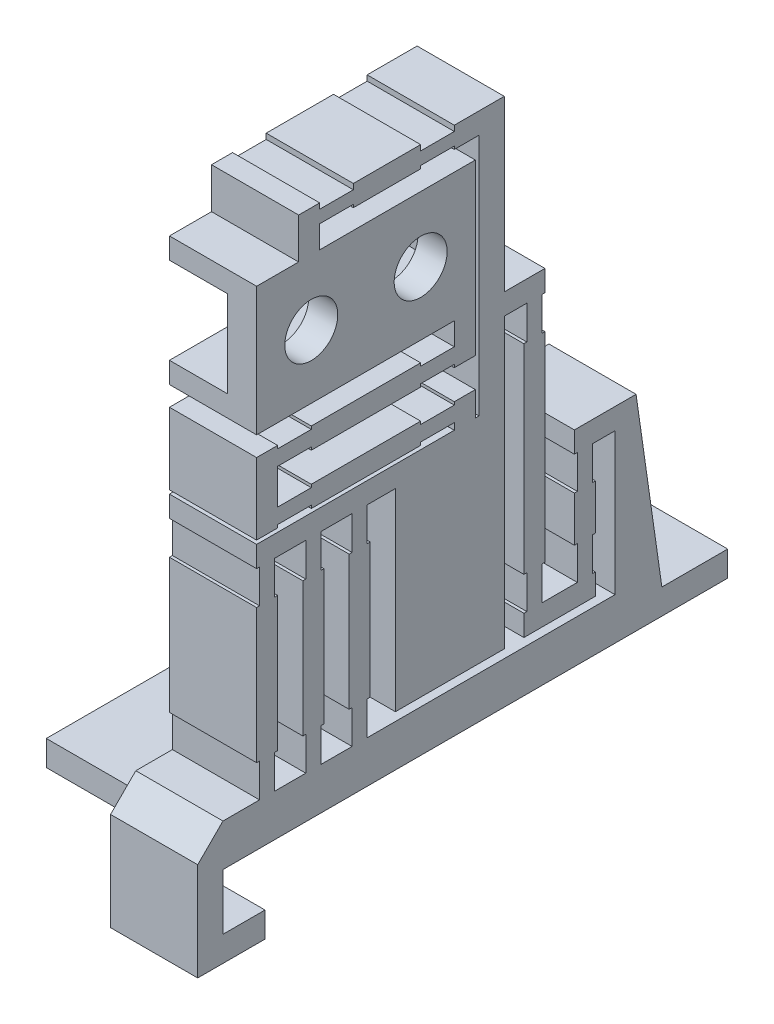
SolidWorks part; units mm, degrees
other "Markup1"
sketch "Sketch8" plane through (10.5, 0, 3) normal (0.7095, 0.0467, 0.7031) x (0.7044, -0.0184, -0.7096)
ref_plane "Front Plane" through (0, 0, 0) normal (0, 0, 1) x (1, 0, 0)
ref_plane "Top Plane" through (0, 0, 0) normal (0, 1, 0) x (1, 0, 0)
ref_plane "Right Plane" through (0, 0, 0) normal (1, 0, 0) x (0, 0, -1)
sketch "Sketch1" plane through (0, 0, 0) normal (1, 0, 0) x (0, 0, -1)
  line L0 (5.75, 29.025) -> (15, 29.025)
  line L1 (15, 29.025) -> (15, 18.9583)
  line L2 (2, 29.025) -> (2, 21.375)
  line L3 (2, 21.375) -> (13.75, 21.375)
  line L56 (13.75, 20.0333) -> (11.75, 20.0333)
  line L57 (3.25, 19.1333) -> (3.25, 17.0333)
  line L58 (3.25, 17.0333) -> (5.25, 17.0333)
  line L59 (15, 17.2083) -> (15, 15.7383)
  line L60 (13.75, 21.375) -> (13.75, 20.0333)
  line L61 (11.75, 20.0333) -> (11.75, 20.2083)
  line L62 (2, 20.2083) -> (2, 15.9583)
  line L63 (5.25, 17.0333) -> (5.25, 17.2083)
  line L64 (15.22, 30.1917) -> (15.22, 15.7383)
  line L65 (5.75, 30.3667) -> (7.75, 30.3667)
  line L66 (13.75, 31.1167) -> (13.75, 31.4417)
  line L69 (5.75, 29.025) -> (5.75, 30.3667)
  line L70 (7.75, 30.3667) -> (7.75, 30.1917)
  line L76 (7.75, 30.1917) -> (11.75, 30.1917)
  line L77 (11.75, 30.1917) -> (11.75, 30.3667)
  line L78 (11.75, 30.3667) -> (13.75, 30.3667)
  line L79 (13.75, 30.3667) -> (13.75, 30.1917)
  line L80 (13.75, 30.1917) -> (15.22, 30.1917)
  line L81 (13.75, 31.1167) -> (11.75, 31.1167)
  line L82 (11.75, 31.1167) -> (11.75, 31.4417)
  line L83 (11.75, 31.4417) -> (7.75, 31.4417)
  line L84 (7.75, 31.4417) -> (7.75, 31.1167)
  line L85 (7.75, 31.1167) -> (5.75, 31.1167)
  line L86 (5.75, 31.1167) -> (5.75, 31.4417)
  line L87 (5.75, 31.4417) -> (4.5, 31.4417)
  line L100 (11.75, 20.2083) -> (5.25, 20.2083)
  line L101 (5.25, 20.2083) -> (5.25, 20.0333)
  line L102 (5.25, 20.0333) -> (3.25, 20.0333)
  line L103 (3.25, 20.0333) -> (3.25, 20.2083)
  line L104 (3.25, 20.2083) -> (2, 20.2083)
  line L105 (15, 18.9583) -> (13.75, 18.9583)
  line L106 (13.75, 18.9583) -> (13.75, 19.1333)
  line L107 (13.75, 19.1333) -> (11.75, 19.1333)
  line L108 (11.75, 19.1333) -> (11.75, 18.9583)
  line L109 (11.75, 18.9583) -> (5.25, 18.9583)
  line L110 (5.25, 18.9583) -> (5.25, 19.1333)
  line L111 (5.25, 19.1333) -> (3.25, 19.1333)
  line L112 (5.25, 17.2083) -> (11.75, 17.2083)
  line L113 (11.75, 17.2083) -> (11.75, 17.0333)
  line L114 (11.75, 17.0333) -> (13.75, 17.0333)
  line L115 (13.75, 17.0333) -> (13.75, 17.2083)
  line L116 (13.75, 17.2083) -> (15, 17.2083)
  line L117 (2, 15.9583) -> (3.25, 15.9583)
  line L118 (3.25, 15.9583) -> (3.25, 16.1333)
  line L119 (3.25, 16.1333) -> (5.25, 16.1333)
  line L120 (5.25, 16.1333) -> (5.25, 15.9583)
  line L121 (5.25, 15.9583) -> (11.75, 15.9583)
  line L122 (11.75, 15.9583) -> (11.75, 16.1333)
  line L123 (11.75, 16.1333) -> (13.75, 16.1333)
  line L124 (13.75, 16.1333) -> (13.75, 15.7383)
  line L125 (15.22, 15.7383) -> (15, 15.7383)
  line L126 (13.75, 15.7383) -> (2, 15.7383)
  line L127 (2, 15.7383) -> (2, 14.4883)
  line L128 (2, 14.4883) -> (2.175, 14.4883)
  line L130 (21.0617, 4.25) -> (18.9617, 4.25)
  line L131 (18.9617, 4.25) -> (18.9617, 6.25)
  line L132 (18.9617, 6.25) -> (19.1367, 6.25)
  line L133 (19.1367, 6.25) -> (19.1367, 18.125)
  line L134 (19.1367, 18.125) -> (18.9617, 18.125)
  line L135 (18.9617, 18.125) -> (18.9617, 20.125)
  line L136 (18.9617, 20.125) -> (19.1367, 20.125)
  line L137 (21.0617, 10.9375) -> (21.0617, 8.9375)
  line L138 (21.0617, 8.9375) -> (20.8867, 8.9375)
  line L139 (20.8867, 8.9375) -> (20.8867, 6.25)
  line L140 (20.8867, 6.25) -> (21.0617, 6.25)
  line L141 (21.0617, 6.25) -> (21.0617, 4.25)
  line L145 (18.0617, 4.25) -> (17.8867, 4.25)
  line L146 (18.0617, 4.25) -> (18.0617, 6.25)
  line L147 (18.0617, 6.25) -> (17.8867, 6.25)
  line L148 (17.8867, 6.25) -> (17.8867, 18.125)
  line L149 (17.8867, 18.125) -> (18.0617, 18.125)
  line L150 (18.0617, 20.125) -> (16.72, 20.125)
  line L151 (18.0617, 18.125) -> (18.0617, 20.125)
  line L153 (16.72, 21.375) -> (19.1367, 21.375)
  line L155 (23.3033, 10.9375) -> (21.9617, 10.9375)
  line L156 (21.9617, 10.9375) -> (21.9617, 8.9375)
  line L157 (21.9617, 8.9375) -> (22.1367, 8.9375)
  line L158 (22.1367, 8.9375) -> (22.1367, 6.25)
  line L159 (22.1367, 6.25) -> (21.9617, 6.25)
  line L160 (21.9617, 6.25) -> (21.9617, 4.25)
  line L168 (23.3033, 2.5) -> (23.3033, 10.9375)
  line L179 (23.3033, 2.5) -> (8.575, 2.5)
  line L184 (0, 0) -> (26.3033, 0)
  line L189 (16.72, 3) -> (16.72, 20.125)
  line L192 (22.1367, 4.25) -> (21.9617, 4.25)
  line L198 (17.8867, 4.25) -> (17.8867, 3)
  line L199 (22.1367, 4.25) -> (22.1367, 3)
  line L200 (22.1367, 3) -> (17.8867, 3)
  line L201 (16.72, 21.375) -> (16.72, 31.4417)
  line L203 (20.8867, 10.9375) -> (20.8867, 12.1875)
  line L204 (19.1367, 20.125) -> (19.1367, 21.375)
  line L205 (20.8867, 10.9375) -> (21.0617, 10.9375)
  line L208 (0, 0) -> (0, -3.33)
  line L209 (0, -3.33) -> (2.5, -3.33)
  line L210 (2.5, -3.33) -> (2.5, -4.83)
  line L211 (2.5, -4.83) -> (-1.5, -4.83)
  line L212 (-1.5, -4.83) -> (-1.5, 1)
  line L213 (-1.5, 1) -> (0, 2.5)
  line L214 (4.5, 29.025) -> (2, 29.025)
  line L215 (4.5, 29.025) -> (4.5, 31.4417)
  line L220 (15.395, 0) -> (15.395, 2.5) construction
  line L221 (13.75, 31.4417) -> (16.72, 31.4417)
  line L222 (20.8867, 12.1875) -> (24.5533, 12.1875)
  line L224 (16.72, 3) -> (10.25, 3)
  line L225 (10.25, 3) -> (10.25, 14.4883)
  line L226 (24.5533, 12.1875) -> (26.3033, 0)
  line L227 (3.075, 2.5) -> (3.075, 4.5)
  line L228 (3.075, 4.5) -> (3.25, 4.5)
  line L229 (3.25, 4.5) -> (3.25, 12.4883)
  line L230 (3.25, 12.4883) -> (3.075, 12.4883)
  line L231 (3.075, 12.4883) -> (3.075, 14.4883)
  line L232 (2.175, 2.5) -> (2.175, 4.5)
  line L233 (2.175, 4.5) -> (2, 4.5)
  line L234 (2, 4.5) -> (2, 12.4883)
  line L235 (2, 12.4883) -> (2.175, 12.4883)
  line L236 (2.175, 12.4883) -> (2.175, 14.4883)
  line L237 (5.825, 2.5) -> (5.825, 4.5)
  line L238 (5.825, 4.5) -> (6, 4.5)
  line L239 (6, 4.5) -> (6, 12.4883)
  line L240 (6, 12.4883) -> (5.825, 12.4883)
  line L241 (5.825, 12.4883) -> (5.825, 14.4883)
  line L242 (4.925, 2.5) -> (4.925, 4.5)
  line L243 (4.925, 4.5) -> (4.75, 4.5)
  line L244 (4.75, 4.5) -> (4.75, 12.4883)
  line L245 (4.75, 12.4883) -> (4.925, 12.4883)
  line L246 (4.925, 12.4883) -> (4.925, 14.4883)
  line L247 (8.575, 2.5) -> (8.575, 4.5)
  line L248 (8.575, 4.5) -> (8.75, 4.5)
  line L249 (8.75, 4.5) -> (8.75, 12.4883)
  line L250 (8.75, 12.4883) -> (8.575, 12.4883)
  line L251 (8.575, 12.4883) -> (8.575, 14.4883)
  line L252 (7.675, 2.5) -> (7.675, 4.5)
  line L253 (7.675, 4.5) -> (7.5, 4.5)
  line L254 (7.5, 4.5) -> (7.5, 12.4883)
  line L255 (7.5, 12.4883) -> (7.675, 12.4883)
  line L256 (7.675, 12.4883) -> (7.675, 14.4883)
  line L257 (3.075, 14.4883) -> (4.925, 14.4883)
  line L258 (5.825, 14.4883) -> (7.675, 14.4883)
  line L259 (8.575, 14.4883) -> (10.25, 14.4883)
  line L260 (7.675, 2.5) -> (5.825, 2.5)
  line L261 (4.925, 2.5) -> (3.075, 2.5)
  line L262 (2.175, 2.5) -> (0, 2.5)
  circle A6 centre (-5.835, 25.2) radius 5.8278 construction
  circle A7 centre (-1.835, 41.31) radius 9 construction
  point P25 (2, 25.2)
  point P120 (16.47, 25.56)
  point P140 (23.3033, 10.9375)
  point P174 (19.1367, 12.1875)
  point P199 (21.9617, 5.25)
  dimension "D68" = 18
  dimension "D3" = 4.25
  dimension "D4" = 0.175
  dimension "D5" = 1.25
  dimension "D6" = 0.9
  dimension "D7" = 1.75
  dimension "D8" = 0.175
  dimension "D9" = 0.9
  dimension "D10" = 1.1667
  dimension "D14" = 1.1667
  dimension "D15" = 0.175
  dimension "D16" = 1.25
  dimension "D17" = 0.75
  dimension "D25" = 0.22
  dimension "D35" = 2
  dimension "D37" = 1.25
  dimension "D38" = 1.25
  dimension "D40" = 0.22
  dimension "D41" = 1.25
  dimension "D42" = 1.1667
  dimension "D43" = 0.175
  dimension "D44" = 0.9
  dimension "D45" = 1.75
  dimension "D46" = 0.175
  dimension "D47" = 0.9
  dimension "D48" = 1.25
  dimension "D12" = 7.65
  dimension "D20" = 1.5
  dimension "D27" = 1.1667
  dimension "D32" = 2
  dimension "D39" = 13
  dimension "D30" = 2
  dimension "D53" = 1.5
  dimension "D57" = 1.5
  dimension "D58" = 3.33
  dimension "D59" = 4
  dimension "D60" = 1
  dimension "D65" = 2.5
  dimension "D11" = 2
  dimension "D36" = 15.395
  dimension "D66" = 21.23
  dimension "D67" = 25.2
  dimension "D69" = 16.11
  dimension "D70" = 4
  dimension "D13" = 1.25
  dimension "D18" = 2
  dimension "D19" = 1.25
  dimension "D21" = 1.25
  dimension "D23" = 1.25
  dimension "D24" = 1.25
  dimension "D26" = 2
  dimension "D22" = 3
  dimension "D28" = 1.25
  dimension "D29" = 2.5
  dimension "D31" = 0.5
  dimension "D33" = 1.25
  dimension "D34" = 0.175
  dimension "D49" = 2
  dimension "D50" = 1.25
  dimension "D51" = 0.175
  dimension "D52" = 2
  dimension "D54" = 1.25
  dimension "D55" = 0.175
  dimension "D56" = 2
  dimension "D61" = 1.5
  dimension "D62" = 1.5
  dimension "D63" = 1.5
extrude "Boss-Extrude1" add sketch "Sketch1" along normal blind 5.18
sketch "Sketch2" plane through (0, 0, -2) normal (0, 0, 1) x (1, 0, 0)
  line L0 (5.18, 29.025) -> (5.18, 21.375) construction
  line L1 (5.18, 22.625) -> (1.73, 22.625)
  line L2 (5.18, 22.625) -> (5.18, 27.775)
  line L3 (5.18, 27.775) -> (1.73, 27.775)
  line L4 (1.73, 22.625) -> (1.73, 27.775)
  line L5 (5.18, 29.025) -> (5.18, 21.375) construction
  dimension "D1" = 3.45
  dimension "D2" = 1.25
  dimension "D3" = 1.25
extrude "Cut-Extrude4" cut sketch "Sketch2" against normal up to next
sketch "Sketch3" plane through (0, 0, 0) normal (0, -1, 0) x (1, 0, 0)
  line L1 (0, -30) -> (10.5, -30)
  line L2 (0, -30) -> (0, 0)
  line L3 (0, 0) -> (10.5, 0)
  line L4 (10.5, -30) -> (10.5, 0)
  line L5 (5.18, 0) -> (5.18, -26.3033) construction
  line L8 (0, 0) -> (0, -26.3033) construction
  circle A0 centre (7.62, -15.23) radius 1.575
  circle A1 centre (7.62, -27.23) radius 1.575
  dimension "D3" = 3.15
  dimension "D1" = 10.5
  dimension "D2" = 2.44
  dimension "D4" = 12
  dimension "D5" = 30
  dimension "D6" = 15.23
sketch "Sketch7" plane through (0, 0, 0) normal (-1, 0, 0) x (0, 0, 1)
  line L0 (-4.5, 29.025) -> (-2, 29.025) construction
  line L1 (-2, 29.025) -> (-2, 21.375) construction
  circle A0 centre (-5.25, 25.15) radius 1.575
  circle A1 centre (-11.75, 25.15) radius 1.575
  dimension "D1" = 3.15
  dimension "D2" = 3.875
  dimension "D3" = 3.25
  dimension "D4" = 6.5
extrude "Cut-Extrude3" cut sketch "Sketch7" against normal up to next
extrude "Boss-Extrude2" add sketch "Sketch3" against normal blind 1.5
mirror "Mirror1" about plane through (0, 0, 0) normal (-1, 0, 0) of bodies 111
delete or keep bodies "Body-Delete/Keep 1" type delete bodies bodies 111
equation "\"VerticalFlexureWidth\"= 1.3"
equation "\"VerticalFlexureGap\"= 1"
equation "\"VerticalDoubleFlexureWidth\"= 2 * \"VerticalFlexureWidth\" + \"VerticalFlexureGap\""
equation "\"HorizontalFlexureLength\"= 7"
equation "\"FlexureJointWidth\"= 1.25"
equation "\"HeadHeight\"= 7.5"
equation "\"VerticalFlexureLength\"= 18"
equation "\"MinGap\"= 0.22"
equation "\"BaseplateHeight+Tolerance\"= 3.33"
equation "\"HeadWidth\"= 13"
equation "\"D1@Boss-Extrude1\"=5.18"
equation "\"HorizontalFlexureWidth\"= 1"
equation "\"HorizontalFlexureGap\"= 1"
equation "\"HorizontalDoubleFlexureWidth\"= 2 * \"HorizontalFlexureWidth\" + \"HorizontalFlexureGap\""
equation "\"FlexureWidth\"= 0.9"
equation "\"FlexureWideWidth\"=1.25"
equation "\"FlexureGap\"=1.75"
equation "\"TwinFlexureWidth\"= \"FlexureGap\" + 2 * \"FlexureWideWidth\""
equation "\"D3@Sketch1\"=\"TwinFlexureWidth\""
equation "\"FlexureNeckWidth\"= ( \"FlexureWideWidth\" - \"FlexureWidth\" ) / 2"
equation "\"D4@Sketch1\"=\"FlexureNeckWidth\""
equation "\"D5@Sketch1\"=\"FlexureWideWidth\""
equation "\"D6@Sketch1\"=\"FlexureWidth\""
equation "\"D7@Sketch1\"=\"FlexureGap\""
equation "\"D8@Sketch1\"=\"FlexureNeckWidth\""
equation "\"D9@Sketch1\"=\"FlexureWidth\""
equation "\"D10@Sketch1\"=\"FlexureGapEdge\""
equation "\"D14@Sketch1\"=\"FlexureGapEdge\""
equation "\"D15@Sketch1\"=\"FlexureNeckWidth\""
equation "\"D16@Sketch1\"=\"FlexureWideWidth\""
equation "\"FlexureLength\"= 2"
equation "\"MainSupport\"=1.5"
equation "\"D25@Sketch1\"=\"MinGap\""
equation "\"D35@Sketch1\"=\"FlexureLength\""
equation "\"D37@Sketch1\"=\"FlexureJointWidth\""
equation "\"D38@Sketch1\"=\"FlexureJointWidth\""
equation "\"D41@Sketch1\"=\"FlexureWideWidth\""
equation "\"D42@Sketch1\"=\"FlexureGapEdge\""
equation "\"D43@Sketch1\"=\"FlexureNeckWidth\""
equation "\"D44@Sketch1\"=\"FlexureWidth\""
equation "\"D46@Sketch1\"=\"FlexureNeckWidth\""
equation "\"D47@Sketch1\"=\"FlexureWidth\""
equation "\"D48@Sketch1\"=\"FlexureWideWidth\""
equation "\"D27@Sketch1\"=\"FlexureGapEdge\""
equation "\"D32@Sketch1\"=\"FlexureLength\""
equation "\"D30@Sketch1\"=\"FlexureLength\""
equation "\"D53@Sketch1\"=\"MainSupport\""
equation "\"D57@Sketch1\"=\"MainSupport\""
equation "\"D58@Sketch1\"=\"BaseplateHeight+Tolerance\""
equation "\"D39@Sketch1\"=\"HeadWidth\""
equation "\"FlexureGapEdge\"= \"FlexureGap\" * ( 2 / 3 )"
equation "\"FlexurePlateConnectionHeigh\"= 5.15 + 2.5"
equation "\"D12@Sketch1\"=\"FlexurePlateConnectionHeigh\""
equation "\"D45@Sketch1\"=\"FlexureGap\""
equation "\"D11@Sketch1\"=\"FlexureLength\""
equation "\"D13@Sketch1\"=\"FlexureJointWidth\""
equation "\"D19@Sketch1\"=\"FlexureJointWidth\""
equation "\"D21@Sketch1\"=\"FlexureJointWidth\""
equation "\"D23@Sketch1\"=\"FlexureJointWidth\""
equation "\"D24@Sketch1\"=\"FlexureJointWidth\""
equation "\"D26@Sketch1\"=\"FlexureLength\""
equation "\"D28@Sketch1\"=\"FlexureJointWidth\""
